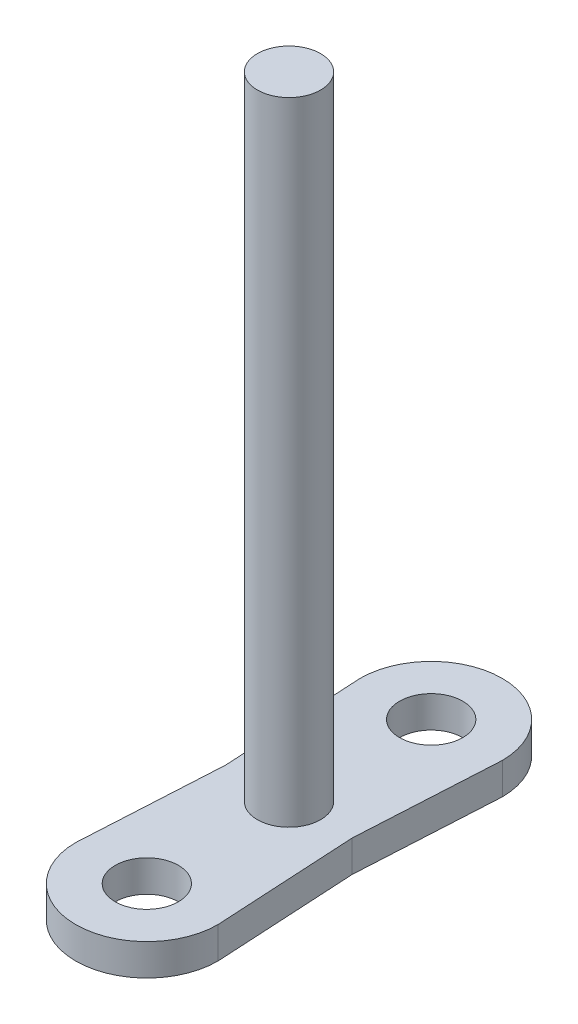
SolidWorks part; units mm, degrees
ref_plane "Front Plane" through (0, 0, 0) normal (0, 0, 1) x (1, 0, 0)
ref_plane "Top Plane" through (0, 0, 0) normal (0, 1, 0) x (1, 0, 0)
ref_plane "Right Plane" through (0, 0, 0) normal (1, 0, 0) x (0, 0, -1)
sketch "Sketch1" plane through (0, 0, 0) normal (0, 1, 0) x (1, 0, 0)
  circle A0 centre (0, 0) radius 2
extrude "Boss-Extrude1" add sketch "Sketch1" along normal blind 40
sketch "Sketch2" plane through (0, 0, 0) normal (0, -1, 0) x (1, 0, 0)
  line L0 (0, 0) -> (0, 9) construction
  line L1 (-4.5, 9) -> (-4, 0)
  line L2 (4.5, 9) -> (4, 0)
  line L3 (0, 0) -> (2.4149, 0) construction
  line L4 (-4.5, -9) -> (-4, 0)
  line L5 (4.5, -9) -> (4, 0)
  circle A0 centre (0, 0) radius 4
  circle A1 centre (0, 9) radius 2
  circle A2 centre (0, 9) radius 4.5
  circle A3 centre (0, -9) radius 2
  circle A4 centre (0, -9) radius 4.5
extrude "Boss-Extrude2" add sketch "Sketch2" along normal blind 2 separate body contours L4 A4 L5 A0 | A4 L4 L5 A3 | A2 L1 A0 L2 | L2 A2 L1 A1
